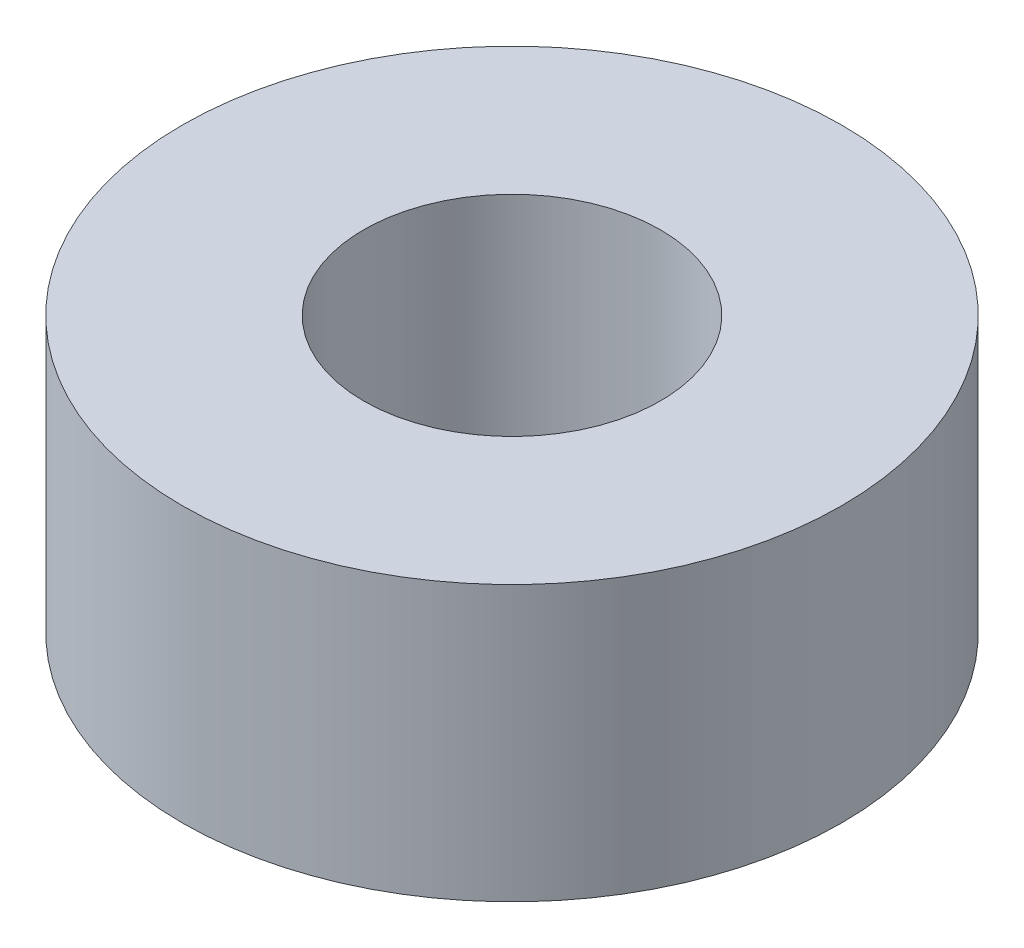
SolidWorks part; units mm, degrees
ref_plane "Front Plane" through (0, 0, 0) normal (0, 0, 1) x (1, 0, 0)
ref_plane "Top Plane" through (0, 0, 0) normal (0, 1, 0) x (1, 0, 0)
ref_plane "Right Plane" through (0, 0, 0) normal (1, 0, 0) x (0, 0, -1)
sketch "Sketch1" plane through (0, 0, 0) normal (0, 1, 0) x (1, 0, 0)
  circle A0 centre (0, 0) radius 3
  circle A1 centre (0, 0) radius 1.35
  dimension "D1" = 6
  dimension "D2" = 2.7
extrude "Boss-Extrude1" add sketch "Sketch1" along normal blind 2.5
